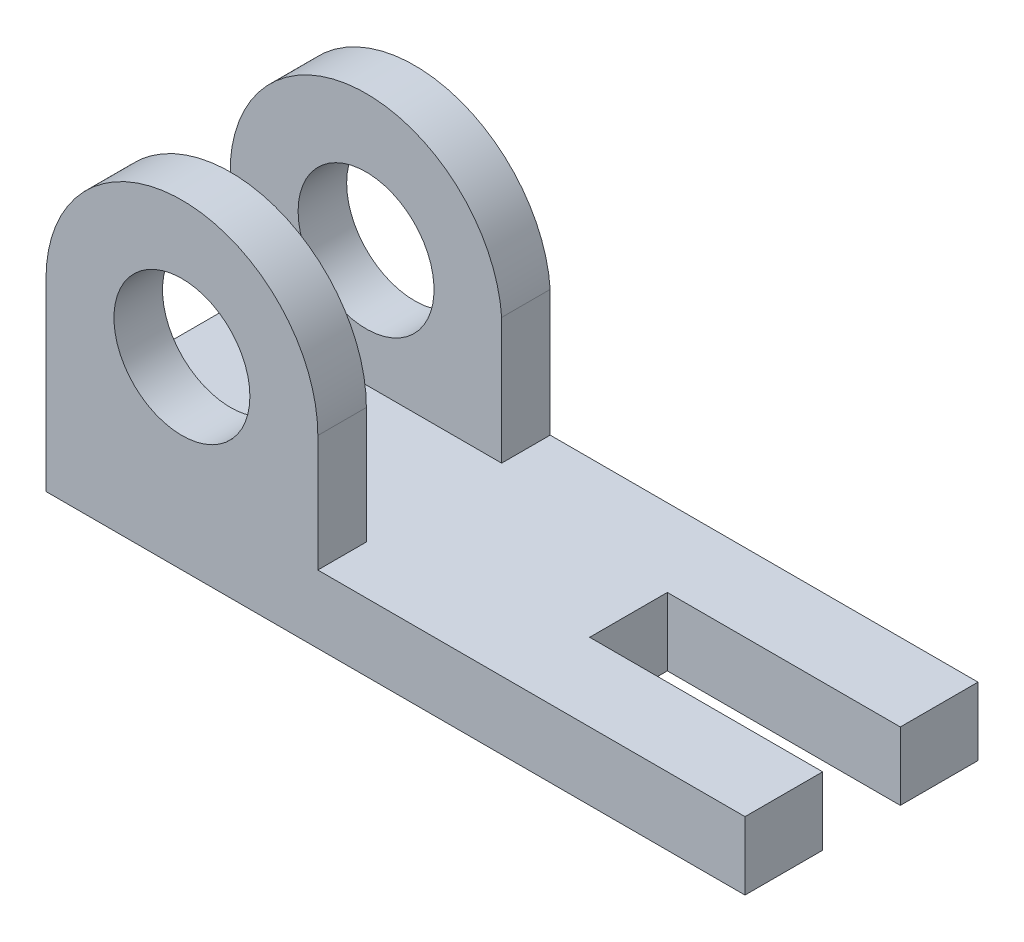
SolidWorks part; units mm, degrees
ref_plane "Front Plane" through (0, 0, 0) normal (0, 0, 1) x (1, 0, 0)
ref_plane "Top Plane" through (0, 0, 0) normal (0, 1, 0) x (1, 0, 0)
ref_plane "Right Plane" through (0, 0, 0) normal (1, 0, 0) x (0, 0, -1)
sketch "Sketch1" plane through (0, 0, 0) normal (0, 0, 1) x (1, 0, 0)
  line L1 (-57.15, 5.5563) -> (57.15, 5.5563)
  line L2 (-57.15, 5.5563) -> (-57.15, -5.5562)
  line L3 (-57.15, -5.5562) -> (57.15, -5.5562)
  line L4 (57.15, 5.5563) -> (57.15, -5.5562)
  line L5 (-57.15, 5.5563) -> (57.15, -5.5562) construction
  line L6 (-57.15, -5.5562) -> (57.15, 5.5563) construction
  point P0 (0, 0)
  dimension "D1" = 11.1125
  dimension "D2" = 114.3
extrude "Boss-Extrude1" add sketch "Sketch1" along normal mid plane 38.1
sketch "Sketch3" plane through (57.15, 0, 0) normal (1, 0, 0) x (0, 0, -1)
  line L0 (-19.05, -5.5562) -> (19.05, -5.5562) construction
  line L1 (-6.35, 5.5562) -> (6.35, 5.5562)
  line L2 (-6.35, 5.5562) -> (-6.35, -5.5562)
  line L3 (-6.35, -5.5562) -> (6.35, -5.5562)
  line L4 (6.35, 5.5562) -> (6.35, -5.5562)
  line L5 (-6.35, 5.5562) -> (6.35, -5.5562) construction
  line L6 (-6.35, -5.5562) -> (6.35, 5.5562) construction
  point P0 (0, 0)
  dimension "D1" = 12.7
extrude "Cut-Extrude1" cut sketch "Sketch3" against normal blind 38.1
sketch "Sketch4" plane through (0, 0, 19.05) normal (0, 0, 1) x (1, 0, 0)
  line L0 (-34.925, 125.8183) -> (-34.925, -67.4386) construction
  line L1 (-57.15, 5.5563) -> (-12.7, 5.5563)
  line L2 (-57.15, 5.5563) -> (-57.15, 46.8312)
  line L3 (-57.15, 46.8312) -> (-12.7, 46.8312)
  line L4 (-12.7, 5.5563) -> (-12.7, 46.8312)
  line L5 (-90.2537, 24.6062) -> (44.9591, 24.6062) construction
  line L6 (-57.15, -5.5562) -> (57.15, -5.5562) construction
  circle A0 centre (-34.925, 24.6062) radius 11.115
  arc A1 (-57.15, 24.6062) -> (-12.7, 24.6062) centre (-34.925, 24.6062) cw
  point P15 (-34.925, 46.8312)
  point P16 (-34.925, 46.8312)
  line M3 (57.15, 5.5563) -> (-57.15, 5.5563)
  dimension "D2" = 22.225
  dimension "D3" = 22.23
  dimension "D1" = 30.1625
extrude "Boss-Extrude2" add sketch "Sketch4" against normal blind 7.9375 contours A1 L2 L4 A0 M3
sketch "Sketch5" plane through (0, 0, -19.05) normal (0, 0, -1) x (-1, 0, 0)
  line L0 (34.977, -24.9924) -> (34.977, 55.4598) construction
  line L1 (57.15, 5.5563) -> (12.804, 5.5562)
  line L2 (57.15, 5.5563) -> (57.15, 46.8338)
  line L3 (57.15, 46.8338) -> (12.804, 46.8338)
  line L4 (12.804, 5.5562) -> (12.804, 46.8338)
  line L5 (67.921, 24.6038) -> (0.84, 24.6037) construction
  line L6 (57.15, -5.5562) -> (-57.15, -5.5562) construction
  circle A0 centre (34.977, 24.6038) radius 11.1125
  arc A1 (12.804, 26.195) -> (57.15, 26.195) centre (34.977, 24.6038) cw
  point P15 (34.977, 46.8338)
  point P16 (34.977, 46.8338)
  line M4 (57.15, 5.5563) -> (-57.15, 5.5563)
  dimension "D1" = 22.23
  dimension "D2" = 22.225
  dimension "D3" = 30.16
extrude "Boss-Extrude3" add sketch "Sketch5" against normal blind 7.9375 contours A1 L4 L2 A0 M4
